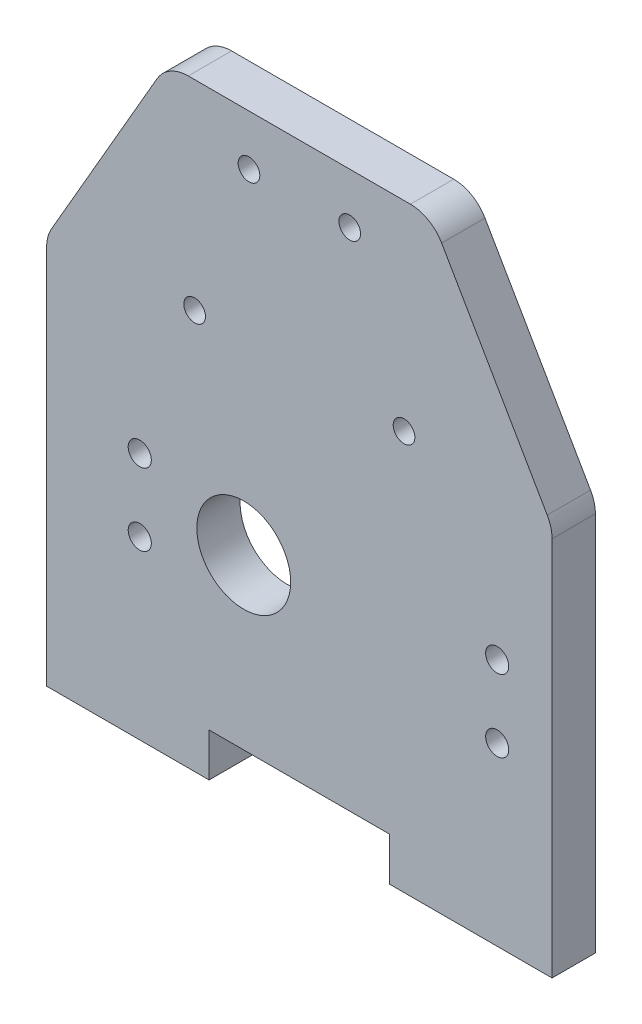
SolidWorks part; units mm, degrees
ref_plane "Front Plane" through (0, 0, 0) normal (0, 0, 1) x (1, 0, 0)
ref_plane "Top Plane" through (0, 0, 0) normal (0, 1, 0) x (1, 0, 0)
ref_plane "Right Plane" through (0, 0, 0) normal (1, 0, 0) x (0, 0, -1)
ref_plane "Plane1"
sketch "Sketch1" plane through (0, 0, 0) normal (0, 0, 1) x (1, 0, 0)
  line L0 (35, -40) -> (35, 14.0192)
  line L1 (35, 14.0192) -> (20, 40)
  line L2 (20, 40) -> (0, 40)
  line L3 (0, 40) -> (0, -40)
  line L4 (0, -40) -> (35, -40)
  dimension "D1" = 150
extrude "Extrusion1" add sketch "Sketch1" along normal blind 6
ref_plane "Plane2" through (0, -8, 3) normal (-1, 0, 0) x (0, -1, 0)
mirror "Mirror1" about plane through (0, -8, 3) normal (-1, 0, 0) of "Extrusion1"
hole_wizard "Hole1" positions "Sketch3" profile "Sketch2" legacy end condition through all
sketch "Sketch3" plane through (0, 0, 0) normal (0, 0, -1) x (-1, 0, 0)
  point P1 (-6.9756, 36)
  point P2 (-14.5, 15.3268)
  point P3 (14.5, 15.3268)
  point P4 (6.9756, 36)
sketch "Sketch2" plane through (6.9756, 36, 0) normal (1, 0, 0) x (0, 1, 0)
  line L0 (0, 0) -> (0, 6)
  line L1 (0, 6) -> (1.5, 6)
  line L2 (1.5, 6) -> (1.5, 0)
  line L3 (1.5, 0) -> (0, 0)
  line L4 (0, 110) -> (0, -10) construction
  dimension "Diameter" = 3
  dimension "Depth" = 6
hole_wizard "Hole2" positions "Sketch5" profile "Sketch4" legacy end condition through all
sketch "Sketch5" plane through (0, 0, 6) normal (0, 0, 1) x (1, 0, 0)
  point P1 (-22.1, -5.6299)
  point P2 (-22.1, -15.6299)
  point P3 (27.4, -15.6299)
  point P4 (27.4, -5.6299)
sketch "Sketch4" plane through (-22.1, -5.6299, 6) normal (1, 0, 0) x (0, -1, 0)
  line L0 (0, 0) -> (0, 6)
  line L1 (0, 6) -> (1.6, 6)
  line L2 (1.6, 6) -> (1.6, 0)
  line L3 (1.6, 0) -> (0, 0)
  line L4 (0, 110) -> (0, -10) construction
  dimension "Diameter" = 3.2
  dimension "Depth" = 6
sketch "Sketch6" plane through (0, 0, 0) normal (0, 0, -1) x (-1, 0, 0)
  line L0 (12.5, -34) -> (-12.5, -34)
  line L1 (-12.5, -34) -> (-12.5, -40)
  line L2 (-12.5, -40) -> (12.5, -40)
  line L3 (12.5, -40) -> (12.5, -34)
  line L4 (35, -40) -> (35, 14.0192) construction
  line L5 (35, 14.0192) -> (20, 40) construction
  circle A0 centre (-14.5, 15.3268) radius 1.5 construction
  circle A1 centre (-6.9756, 36) radius 1.5 construction
  dimension "D1" = 22
  dimension "D2" = 150
  dimension "D3" = 6
  dimension "D4" = 25
extrude "Extrusion3" cut sketch "Sketch6" against normal blind 10
sketch "Sketch7" plane through (0, 0, 6) normal (0, 0, 1) x (1, 0, 0)
  line L0 (-20, 40) -> (-18.2679, 43)
  line L1 (-18.2679, 43) -> (18.2679, 43)
  line L2 (18.2679, 43) -> (20, 40)
  line L3 (20, 40) -> (-20, 40)
  dimension "D1" = 3
extrude "Extrusion4" add sketch "Sketch7" against normal blind 6
fillet "Fillet1" radius 5 4 edges at (-35, 14.0192, 3) (-18.2679, 43, 3) (35, 14.0192, 3) (18.2679, 43, 3)
sketch "Sketch8" plane through (0, 0, 6) normal (0, 0, 1) x (1, 0, 0)
  circle A0 centre (-7.7, -10.6299) radius 6.5
  dimension "D1" = 13
extrude "Extrusion5" cut sketch "Sketch8" against normal blind 10
